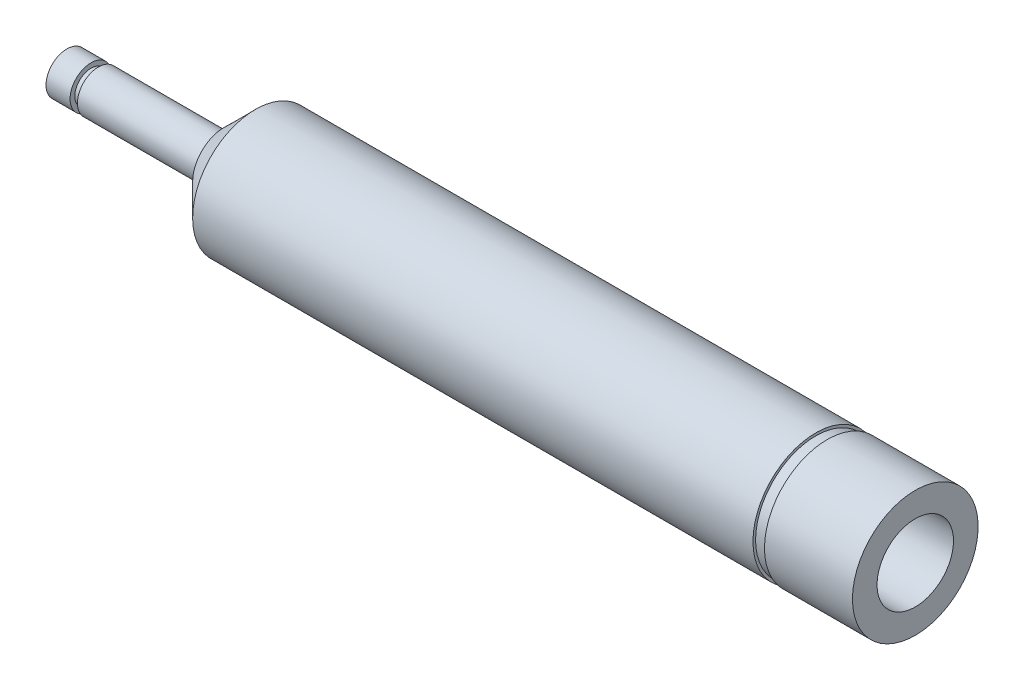
SolidWorks part; units mm, degrees
ref_plane "Plan1" through (0, 0, 0) normal (0, 0, 1) x (1, 0, 0)
ref_plane "Plan2" through (0, 0, 0) normal (0, 1, 0) x (1, 0, 0)
ref_plane "Plan3" through (0, 0, 0) normal (1, 0, 0) x (0, 0, -1)
sketch "Esquisse1" plane through (0, 0, 0) normal (0, 0, 1) x (1, 0, 0)
  line L0 (0, 0) -> (0, 6)
  line L1 (0, 6) -> (-8.4, 6)
  line L2 (-8.4, 6) -> (-8.4, 5.75)
  line L3 (-8.4, 5.75) -> (-9.5, 5.75)
  line L4 (-9.5, 5.75) -> (-9.5, 6)
  line L5 (-9.5, 6) -> (-63, 6)
  line L6 (-63, 6) -> (-66, 3)
  line L7 (-66, 3) -> (-66, 2)
  line L8 (-66, 2) -> (-78, 2)
  line L9 (-78, 2) -> (-78, 1.55)
  line L10 (-78, 1.55) -> (-78.7, 1.55)
  line L11 (-78.7, 1.55) -> (-78.7, 2)
  line L12 (-78.7, 2) -> (-81, 2)
  line L13 (-81, 2) -> (-81, 0)
  line L14 (-81, 0) -> (0, 0)
  line L15 (-95.7958, 0) -> (15.6644, 0) construction
  dimension "D1" = 45
  dimension "D2" = 5.75
  dimension "D3" = 6
  dimension "D4" = 6
  dimension "D5" = 2
  dimension "D6" = 1.55
  dimension "D7" = 2
  dimension "D8" = 66
  dimension "D9" = 81
  dimension "D10" = 9.5
  dimension "D11" = 1.1
  dimension "D12" = 0.7
  dimension "D13" = 12
  dimension "D14" = 3
revolve "Base-Révolution" add sketch "Esquisse1" angle 360 about L15
hole_wizard "Perçage1" positions "Esquisse3" profile "Esquisse2" legacy
sketch "Esquisse3" plane through (0, 0, 0) normal (1, 0, 0) x (0, 0, -1)
  point P0 (0, 0)
sketch "Esquisse2" plane through (0, 0, 0) normal (0, 1, 0) x (0, 0, -1)
  line L0 (0, 0) -> (0, 36.5877)
  line L1 (0, 36.5877) -> (2.75, 35)
  line L2 (2.75, 35) -> (2.75, 13)
  line L3 (2.75, 13) -> (3.65, 13)
  line L4 (3.65, 0) -> (0, 0)
  line L5 (0, -11.3109) -> (0, 121.1557) construction
  line L6 (0, 36.5877) -> (-2.75, 35) construction
  line L7 (3.65, 13) -> (3.65, 0)
  dimension "Diamètre" = 5.5
  dimension "Profondeur" = 35
  dimension "Diamètre chambrage" = 7.3
  dimension "Profondeur chambrage" = 13
  dimension "Angle" = 120
